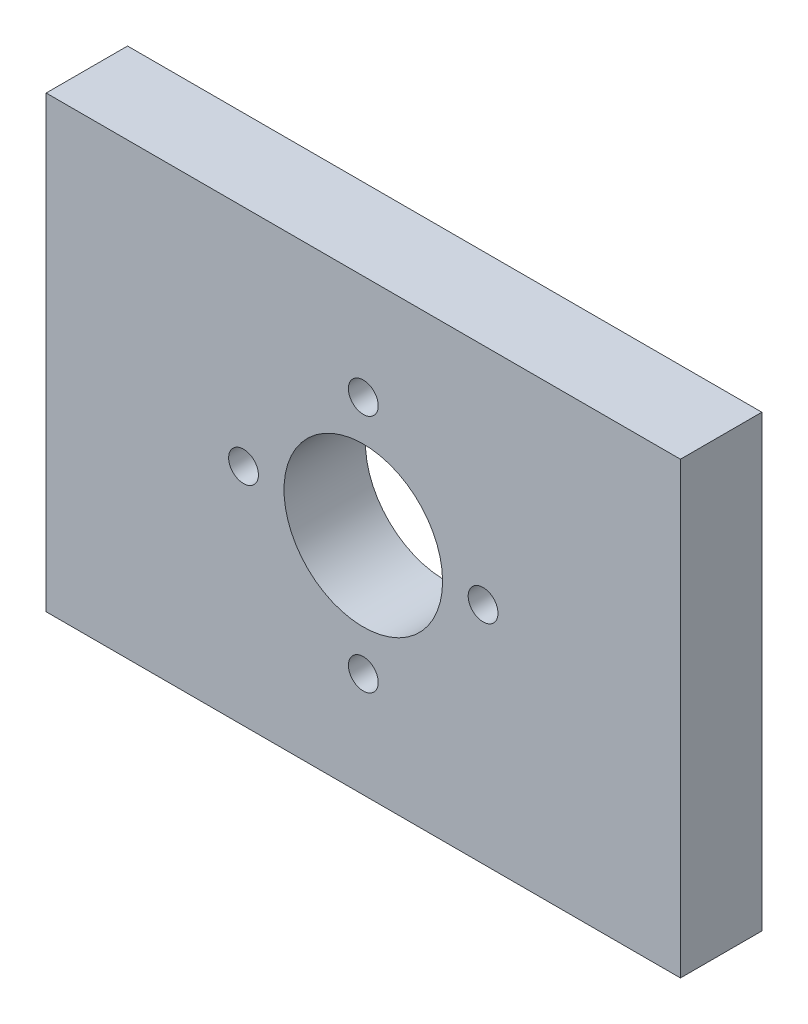
SolidWorks part; units mm, degrees
ref_plane "Front Plane" through (0, 0, 0) normal (1, 0, 0) x (0, 1, 0)
ref_plane "Top Plane" through (0, 0, 0) normal (0, 0, 1) x (0, 1, 0)
ref_plane "Right Plane" through (0, 0, 0) normal (0, 1, 0) x (-1, 0, 0)
sketch "Sketch2" plane through (0, 0, 0) normal (0, 0, 1) x (0, 1, 0)
  line L1 (-53.975, -76.2) -> (53.975, -76.2)
  line L2 (-53.975, -76.2) -> (-53.975, 76.2)
  line L3 (-53.975, 76.2) -> (53.975, 76.2)
  line L4 (53.975, -76.2) -> (53.975, 76.2)
  line L5 (-53.975, -76.2) -> (53.975, 76.2) construction
  line L6 (-53.975, 76.2) -> (53.975, -76.2) construction
  point P0 (0, 0)
  dimension "D1" = 152.4
  dimension "D2" = 107.95
extrude "Boss-Extrude1" add sketch "Sketch2" along normal blind 19.558
sketch "Sketch33" plane through (0, 0, 19.558) normal (0, 0, 1) x (1, 0, 0)
  line L0 (-76.2, 53.975) -> (76.2, -53.975) construction
  line L1 (76.2, 53.975) -> (-76.2, -53.975) construction
  circle A0 centre (0, 0) radius 19.05
  dimension "D1" = 38.1
extrude "Cut-Extrude4" cut sketch "Sketch33" against normal through all
sketch "Sketch35" plane through (0, 0, 19.558) normal (0, 0, 1) x (1, 0, 0)
  line L1 (-28.7782, 0) -> (28.7782, 0) construction
  line L2 (0, -28.7782) -> (0, 28.7782) construction
  circle A0 centre (0, 28.7782) radius 3.5814
  circle A1 centre (28.7782, 0) radius 3.5814
  circle A2 centre (0, -28.7782) radius 3.5814
  circle A3 centre (-28.7782, 0) radius 3.5814
  point P0 (0, 0)
  point P9 (0, 0)
  dimension "D3" = 7.1628
  dimension "D4" = 7.1628
  dimension "D5" = 7.1628
  dimension "D6" = 7.1628
  dimension "D1" = 57.5564
  dimension "D2" = 57.5564
extrude "Cut-Extrude5" cut sketch "Sketch35" against normal through all
